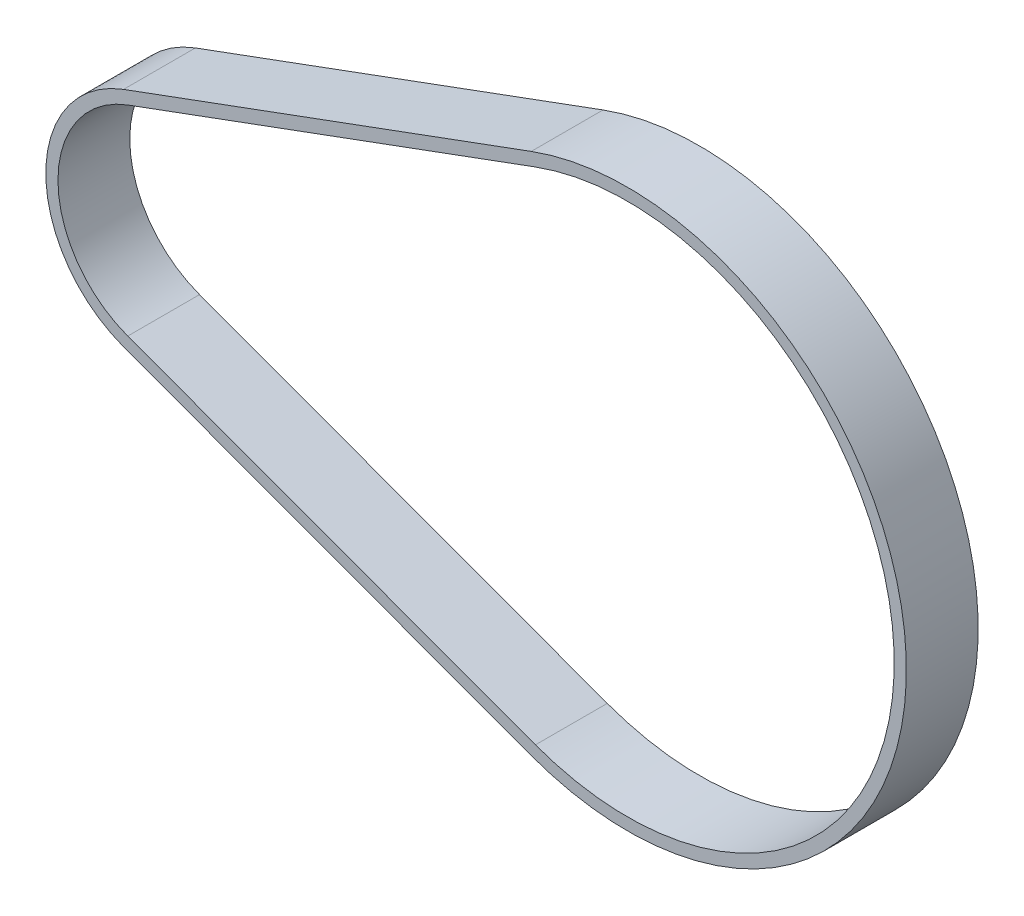
SolidWorks part; units mm, degrees
ref_plane "Front Plane" through (0, 0, 0) normal (0, 0, 1) x (1, 0, 0)
ref_plane "Top Plane" through (0, 0, 0) normal (0, 1, 0) x (1, 0, 0)
ref_plane "Right Plane" through (0, 0, 0) normal (1, 0, 0) x (0, 0, -1)
sketch "Sketch1" plane through (0, 0, 0) normal (0, 0, 1) x (1, 0, 0)
  line L0 (96.7232, 0) -> (0, 0) construction
  line L2 (77.4732, -52.2702) -> (-7.6983, -20.9033)
  line L3 (48.4632, 48.4632) -> (48.4632, 2.5582) construction
  line L6 (-7.6983, 20.9033) -> (77.4732, 52.2702)
  line L7 (76.5954, -54.6537) -> (-8.576, -23.2868)
  line L8 (-8.576, 23.2868) -> (76.5954, 54.6537)
  circle A1 centre (96.7232, 0) radius 55.7022 construction
  arc A3 (77.4732, -52.2702) -> (77.4732, 52.2702) centre (96.7232, 0) ccw
  arc A6 (-7.6983, 20.9033) -> (-7.6983, -20.9033) centre (0, 0) ccw
  arc A7 (76.5954, -54.6537) -> (76.5954, 54.6537) centre (96.7232, 0) ccw
  arc A8 (-8.576, 23.2868) -> (-8.576, -23.2868) centre (0, 0) ccw
  point P19 (0, 0)
  dimension "D1" = 111.4044
  dimension "D4" = 2.54
  dimension "D3" = 44.5516
  dimension "D2" = 96.7232
extrude "Boss-Extrude1" add sketch "Sketch1" along normal blind 15
